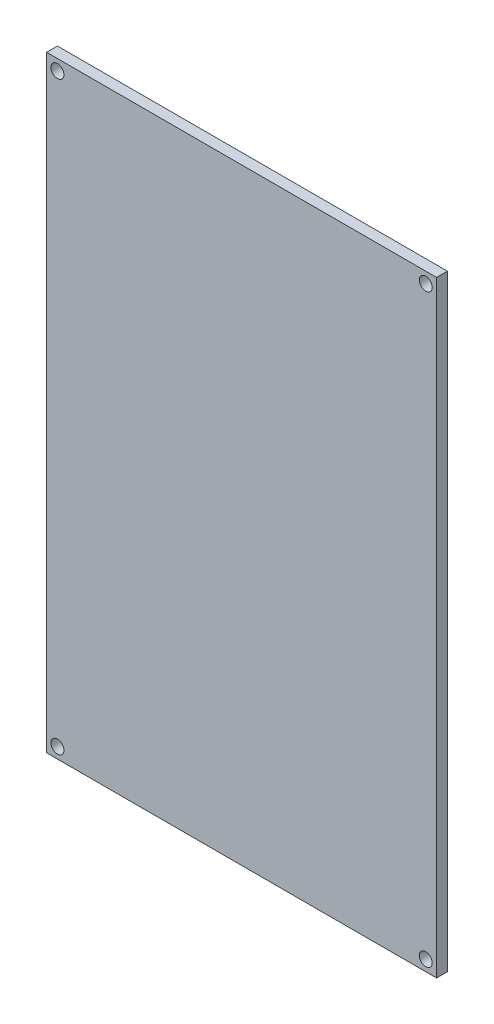
SolidWorks part; units mm, degrees
ref_plane "Front Plane" through (0, 0, 0) normal (0, 0, 1) x (1, 0, 0)
ref_plane "Top Plane" through (0, 0, 0) normal (0, 1, 0) x (1, 0, 0)
ref_plane "Right Plane" through (0, 0, 0) normal (1, 0, 0) x (0, 0, -1)
sketch "Sketch1" plane through (0, 0, 0) normal (0, 0, 1) x (1, 0, 0)
  line L1 (0, 0) -> (114.3, 0)
  line L2 (0, 0) -> (0, 177.8)
  line L3 (0, 177.8) -> (114.3, 177.8)
  line L4 (114.3, 0) -> (114.3, 177.8)
  dimension "D1" = 177.8
  dimension "D2" = 114.3
extrude "Boss-Extrude1" add sketch "Sketch1" along normal blind 3.175
sketch "Sketch2" plane through (0, 0, 3.175) normal (0, 0, 1) x (1, 0, 0)
  line L0 (114.3, 177.8) -> (0, 177.8) construction
  line L1 (0, 177.8) -> (0, 0) construction
  line L2 (114.3, 0) -> (114.3, 177.8) construction
  line L3 (0, 0) -> (114.3, 0) construction
  circle A0 centre (3.175, 174.625) radius 1.905
  circle A1 centre (111.125, 174.625) radius 1.905
  circle A2 centre (111.125, 3.175) radius 1.905
  circle A3 centre (3.175, 3.175) radius 1.905
  dimension "D5" = 3.81
  dimension "D6" = 3.81
  dimension "D9" = 3.81
  dimension "D12" = 3.81
  dimension "D1" = 3.175
  dimension "D2" = 3.175
  dimension "D3" = 3.175
  dimension "D4" = 3.175
  dimension "D7" = 3.175
  dimension "D8" = 3.175
  dimension "D10" = 3.175
  dimension "D11" = 3.175
extrude "Cut-Extrude1" cut sketch "Sketch2" against normal through all
